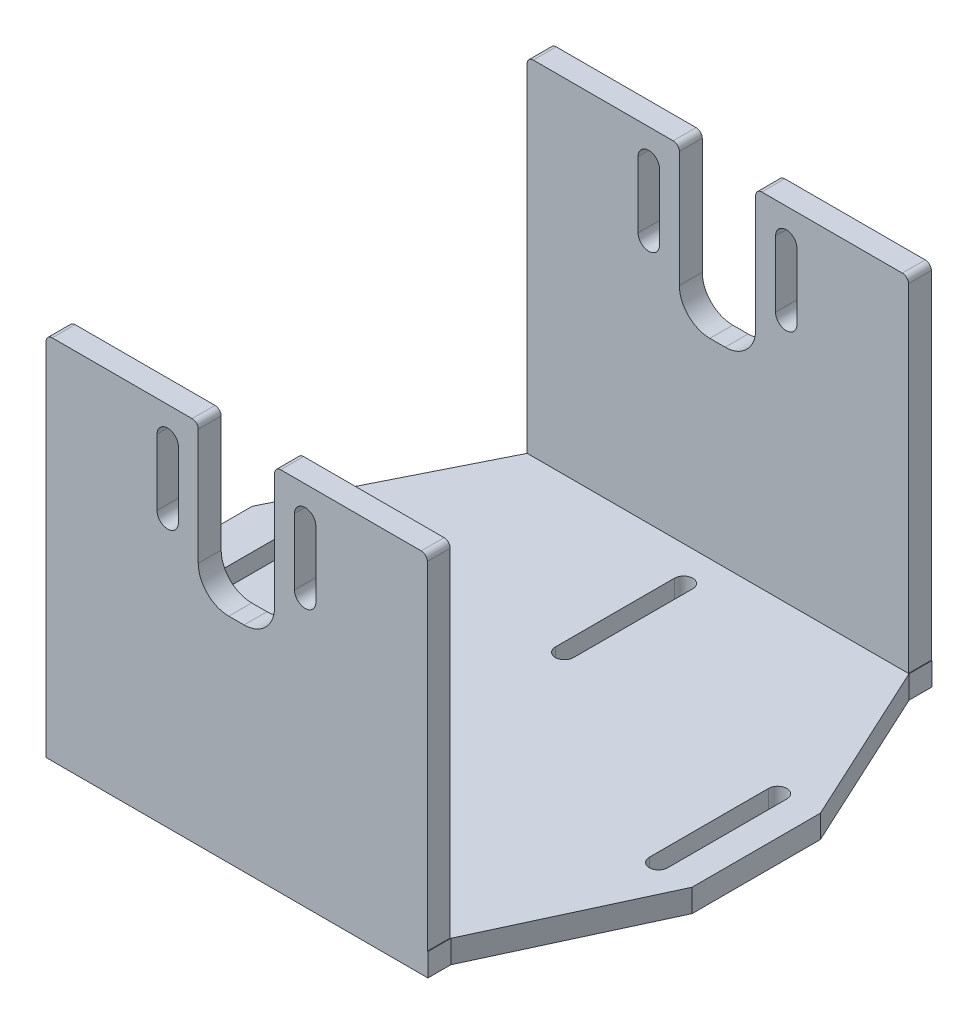
SolidWorks part; units mm, degrees
ref_plane "Front Plane" through (0, 0, 0) normal (0, 0, 1) x (1, 0, 0)
ref_plane "Top Plane" through (0, 0, 0) normal (0, 1, 0) x (1, 0, 0)
ref_plane "Right Plane" through (0, 0, 0) normal (1, 0, 0) x (0, 0, -1)
sketch "Sketch1" plane through (0, 0, 0) normal (0, 1, 0) x (1, 0, 0)
  line L8 (0, -7.5) -> (125, -7.5)
  line L10 (0, 157.5) -> (125, 157.5)
  line L12 (0, -7.5) -> (0, 0)
  line L14 (125, -7.5) -> (125, 0)
  line L15 (0, 157.5) -> (0, 150)
  line L16 (125, 157.5) -> (125, 150)
  line L17 (150, 54) -> (150, 96)
  line L18 (-30, 60) -> (-30, 90)
  line L19 (125, 150) -> (150, 96)
  line L20 (150, 54) -> (125, 0)
  line L21 (0, 0) -> (-30, 60)
  line L22 (-30, 90) -> (0, 150)
  line L23 (137.5, 55.5) -> (137.5, 94.5) construction
  line L24 (134.5, 55.5) -> (134.5, 94.5)
  line L25 (140.5, 55.5) -> (140.5, 94.5)
  line L26 (-14, 55.5) -> (-14, 94.5) construction
  line L27 (-17, 55.5) -> (-17, 94.5)
  line L28 (-11, 55.5) -> (-11, 94.5)
  line L29 (62.5, 11) -> (62.5, 50) construction
  line L30 (59.5, 11) -> (59.5, 50)
  line L31 (65.5, 11) -> (65.5, 50)
  line L32 (62.5, 138.7057) -> (62.5, 99.7057) construction
  line L33 (65.5, 138.7057) -> (65.5, 99.7057)
  line L34 (59.5, 138.7057) -> (59.5, 99.7057)
  arc A0 (134.5, 55.5) -> (140.5, 55.5) centre (137.5, 55.5) ccw
  arc A1 (140.5, 94.5) -> (134.5, 94.5) centre (137.5, 94.5) ccw
  arc A2 (-17, 55.5) -> (-11, 55.5) centre (-14, 55.5) ccw
  arc A3 (-11, 94.5) -> (-17, 94.5) centre (-14, 94.5) ccw
  arc A4 (59.5, 11) -> (65.5, 11) centre (62.5, 11) ccw
  arc A5 (65.5, 50) -> (59.5, 50) centre (62.5, 50) ccw
  arc A6 (65.5, 138.7057) -> (59.5, 138.7057) centre (62.5, 138.7057) ccw
  arc A7 (59.5, 99.7057) -> (65.5, 99.7057) centre (62.5, 99.7057) ccw
  point P4 (0, 0)
  point P5 (0, 0)
  point P18 (137.5, 75)
  point P23 (-14, 75)
  point P30 (62.5, 30.5)
  point P35 (62.5, 119.2057)
sketch "Sketch2" plane through (0, 0, 0) normal (0, 0, 1) x (1, 0, 0)
  line L1 (0, 0) -> (0, 118)
  line L9 (2, 120) -> (47.8128, 120)
  line L10 (49.8128, 118) -> (49.8128, 80)
  line L11 (59.8128, 70) -> (64.8128, 70)
  line L12 (74.8128, 80) -> (74.8128, 118)
  line L13 (76.8128, 120) -> (122.8128, 120)
  line L14 (124.8128, 118) -> (124.8128, 0)
  line L15 (0, 0) -> (124.8128, 0)
  line L16 (39.8128, 88.1904) -> (39.8128, 109.8096) construction
  line L17 (36.3128, 88.1904) -> (36.3128, 109.8096)
  line L18 (43.3128, 88.1904) -> (43.3128, 109.8096)
  line L20 (84.8128, 88.1904) -> (84.8128, 109.8096) construction
  line L21 (88.3128, 88.1904) -> (88.3128, 109.8096)
  line L22 (81.3128, 88.1904) -> (81.3128, 109.8096)
  arc A6 (59.8128, 70) -> (49.8128, 80) centre (59.8128, 80) cw
  arc A7 (64.8128, 70) -> (74.8128, 80) centre (64.8128, 80) ccw
  arc A8 (49.8128, 118) -> (47.8128, 120) centre (47.8128, 118) ccw
  arc A9 (76.8128, 120) -> (74.8128, 118) centre (76.8128, 118) ccw
  arc A10 (2, 120) -> (0, 118) centre (2, 118) ccw
  arc A11 (124.8128, 118) -> (122.8128, 120) centre (122.8128, 118) ccw
  arc A14 (36.3128, 88.1904) -> (43.3128, 88.1904) centre (39.8128, 88.1904) ccw
  arc A15 (43.3128, 109.8096) -> (36.3128, 109.8096) centre (39.8128, 109.8096) ccw
  arc A16 (88.3128, 88.1904) -> (81.3128, 88.1904) centre (84.8128, 88.1904) cw
  arc A17 (81.3128, 109.8096) -> (88.3128, 109.8096) centre (84.8128, 109.8096) cw
  point P23 (49.8128, 99)
  point P24 (39.8128, 99)
  point P32 (84.8128, 99)
  dimension "D3" = 2
  dimension "D4" = 2
  dimension "D5" = 2
  dimension "D6" = 2
extrude "Boss-Extrude6" add sketch "Sketch1" along normal blind 7.5
extrude "Boss-Extrude7" add sketch "Sketch2" along normal blind 7.5
ref_plane "Plane1" through (0, 0, -75) normal (0, 0, -1) x (-1, 0, 0)
mirror "Mirror1" about plane through (0, 0, -75) normal (0, 0, -1) of "Boss-Extrude7"
